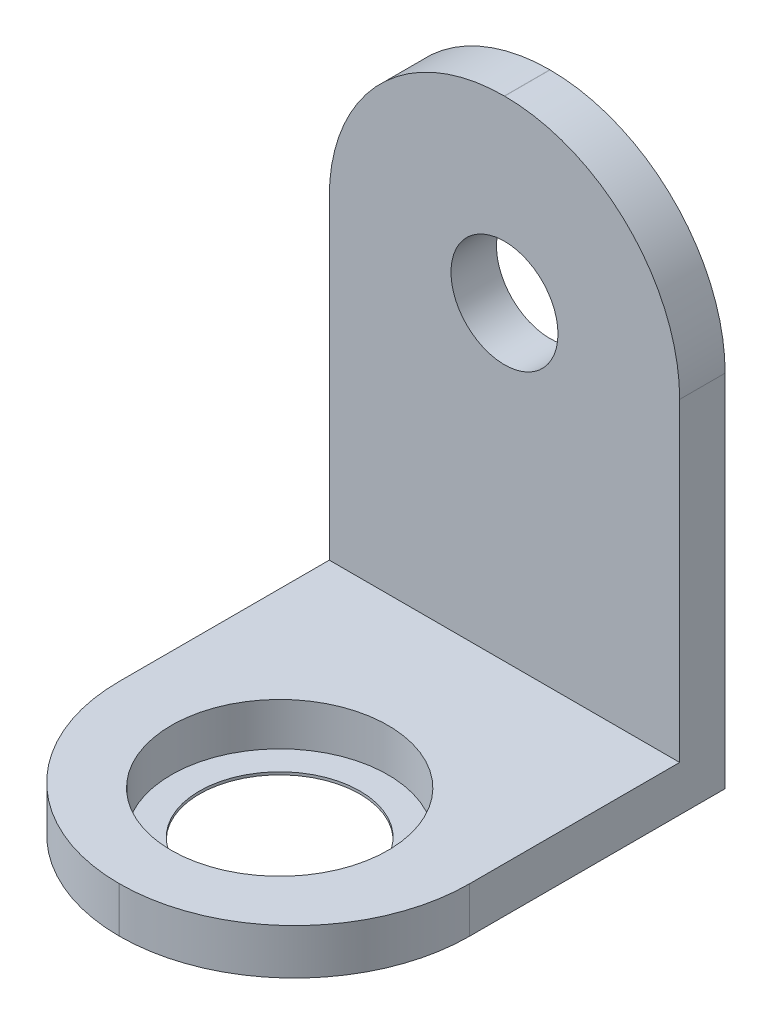
SolidWorks part; units mm, degrees
material "1060 Alloy"
ref_plane "Front Plane" through (0, 0, 0) normal (0, 0, 1) x (1, 0, 0)
ref_plane "Top Plane" through (0, 0, 0) normal (0, 1, 0) x (1, 0, 0)
ref_plane "Right Plane" through (0, 0, 0) normal (1, 0, 0) x (0, 0, -1)
sketch "Sketch2" plane through (0, 0, 0) normal (0, 1, 0) x (1, 0, 0)
  line L1 (-6.446, 10) -> (6.654, 10)
  line L2 (-6.446, 10) -> (-6.446, 0.445)
  line L3 (0.099, -6.1) -> (0.109, -6.1)
  line L4 (6.654, 10) -> (6.654, 0.445)
  circle A0 centre (0, 0) radius 2.5
  arc A1 (0.099, -6.1) -> (-6.446, 0.445) centre (0.099, 0.445) cw
  arc A2 (6.654, 0.445) -> (0.109, -6.1) centre (0.109, 0.445) cw
  point P9 (-6.446, -6.1)
  point P12 (6.654, -6.1)
  dimension "D3" = 5
  dimension "D4" = 6.1
  dimension "D5" = 6.545
  dimension "D6" = 6.545
  dimension "D1" = 13.1
  dimension "D2" = 16.1
extrude "Boss-Extrude1" add sketch "Sketch2" along normal blind 1.7
sketch "Sketch3" plane through (0, 1.7, 0) normal (0, 1, 0) x (1, 0, 0)
  line L0 (6.654, 0.445) -> (6.654, 10) construction
  line L1 (-6.446, 10) -> (6.654, 10)
  line L2 (-6.446, 10) -> (-6.446, 8.3)
  line L3 (-6.446, 8.3) -> (6.654, 8.3)
  line L4 (6.654, 10) -> (6.654, 8.3)
  dimension "D1" = 1.7
extrude "Boss-Extrude2" add sketch "Sketch3" along normal blind 18.3
sketch "Sketch4" plane through (0, 0, -8.3) normal (0, 0, 1) x (1, 0, 0)
  line L0 (-6.446, 20) -> (6.654, 20) construction
  circle A0 centre (0.104, 13.3) radius 2
  dimension "D1" = 4
  dimension "D2" = 6.55
  dimension "D3" = 6.7
extrude "Cut-Extrude1" cut sketch "Sketch4" against normal blind 18.3
fillet "Fillet1" radius 6.545 2 edges at (6.654, 20, -9.15) (-6.446, 20, -9.15)
sketch "Sketch5" plane through (0, 1.7, 0) normal (0, 1, 0) x (1, 0, 0)
  circle A0 centre (0, 0) radius 4.05
  circle A1 centre (0, 0) radius 2.5 construction
  dimension "D1" = 8.1
extrude "Cut-Extrude2" cut sketch "Sketch5" against normal blind 1.6
sketch "Sketch7" plane through (0, 0, 0) normal (0, -1, 0) x (1, 0, 0)
  circle A1 centre (0, 0) radius 1.5
  circle A2 centre (0, 0) radius 2.5
  circle A3 centre (0, 0) radius 2.5
  dimension "D1" = 0
  dimension "D2" = 1
extrude "Boss-Extrude4" add sketch "Sketch7" against normal blind 0.1
sketch "Sketch9" plane through (0, 0, 0) normal (0, -1, 0) x (1, 0, 0)
  circle A0 centre (0, 0) radius 3
  circle A3 centre (0, 0) radius 1.5
  circle A4 centre (0, 0) radius 1.5
  dimension "D1" = 6
  dimension "D2" = 0
extrude "Cut-Extrude3" cut sketch "Sketch9" against normal blind 2
